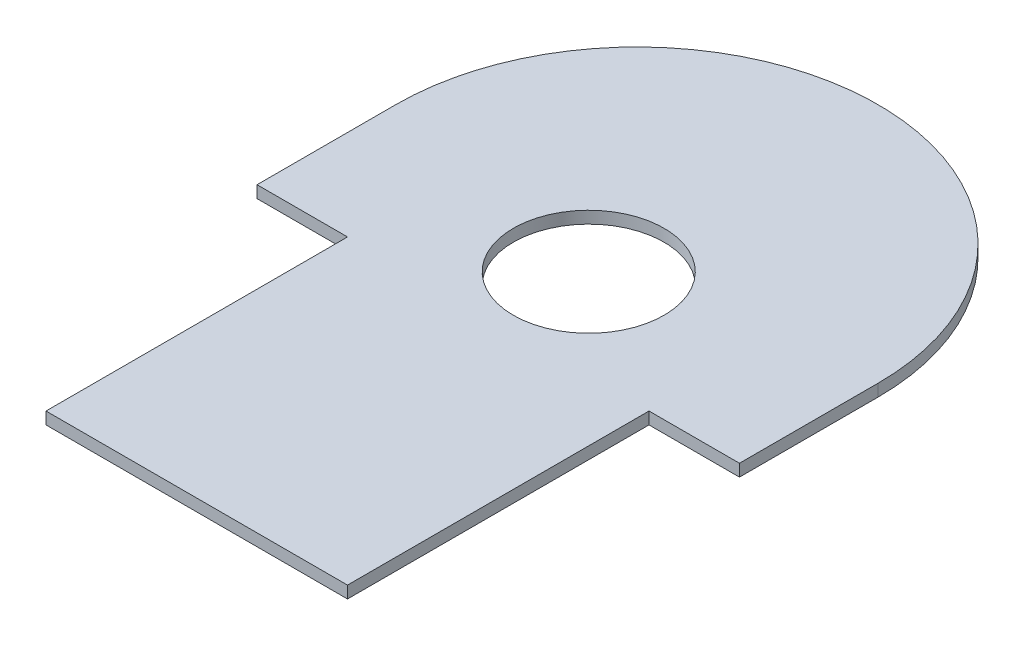
SolidWorks part; units mm, degrees
ref_plane "Front Plane" through (0, 0, 0) normal (0, 0, 1) x (1, 0, 0)
ref_plane "Top Plane" through (0, 0, 0) normal (0, 1, 0) x (1, 0, 0)
ref_plane "Right Plane" through (0, 0, 0) normal (1, 0, 0) x (0, 0, -1)
sketch "Sketch1" plane through (0, 0, 0) normal (0, 1, 0) x (1, 0, 0)
  line L0 (-90.1549, 35.6106) -> (-90.1549, -37.3894)
  line L1 (-90.1549, -37.3894) -> (-10.1549, -37.3894)
  line L2 (-10.1549, -37.3894) -> (-10.1549, 35.6106)
  arc A0 (-10.1549, 35.6106) -> (-90.1549, 35.6106) centre (-50.1549, 35.6106) ccw
  dimension "D1" = 80
  dimension "D2" = 73
extrude "Boss-Extrude1" add sketch "Sketch1" along normal blind 2 contours L0 L1 L2 A0
sketch "Sketch2" plane through (0, 2, 0) normal (0, 1, 0) x (1, 0, 0)
  line L0 (-90.1549, -37.3894) -> (-10.1549, -37.3894) construction
  line L2 (-90.1549, -37.3894) -> (-75.1549, -37.3894)
  line L3 (-90.1549, -37.3894) -> (-90.1549, 12.6106)
  line L4 (-90.1549, 12.6106) -> (-75.1549, 12.6106)
  line L5 (-75.1549, -37.3894) -> (-75.1549, 12.6106)
  line L6 (-10.1549, -37.3894) -> (-25.1549, -37.3894)
  line L7 (-10.1549, -37.3894) -> (-10.1549, 12.6106)
  line L8 (-10.1549, 12.6106) -> (-25.1549, 12.6106)
  line L9 (-25.1549, -37.3894) -> (-25.1549, 12.6106)
  circle A0 centre (-50.1549, 27.6106) radius 12.5
  point P4 (-50.1549, -37.3894)
  dimension "D1" = 25
  dimension "D2" = 65
  dimension "D3" = 50
  dimension "D4" = 15
  dimension "D5" = 15
  dimension "D6" = 50
extrude "Cut-Extrude1" cut sketch "Sketch2" against normal blind 2
